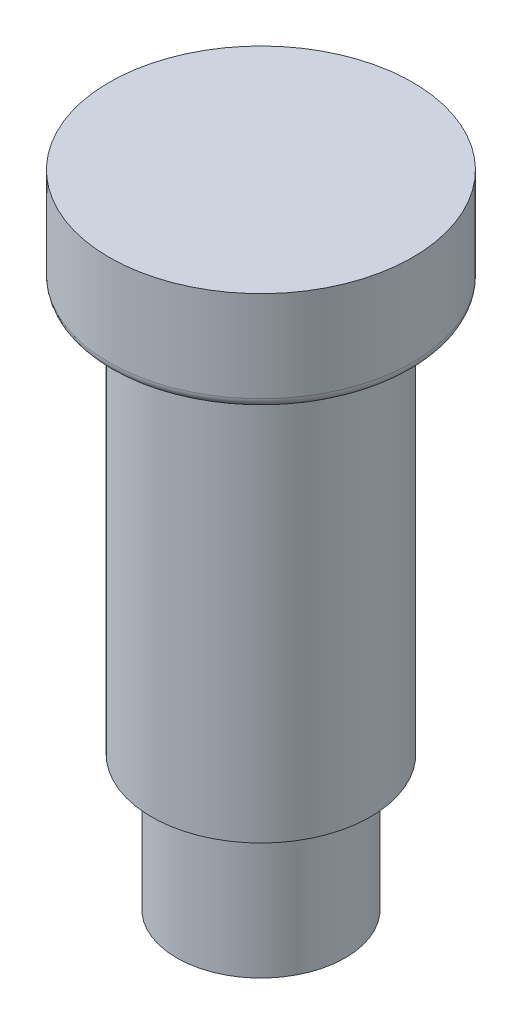
SolidWorks part; units mm, degrees
material "AISI 1020"
ref_plane "Plano superior" through (0, 0, 0) normal (0, 0, 1) x (1, 0, 0)
ref_plane "Plano frontal" through (0, 0, 0) normal (0, 1, 0) x (1, 0, 0)
ref_plane "Plano direito" through (0, 0, 0) normal (1, 0, 0) x (0, 0, -1)
sketch "Esboço1" plane through (0, 0, 0) normal (0, 1, 0) x (1, 0, 0)
  circle A0 centre (0, 0) radius 4.5
  dimension "D1" = 9
extrude "Ressalto-extrusão1" add sketch "Esboço1" along normal blind 3
sketch "Esboço2" plane through (0, 0, 0) normal (0, -1, 0) x (1, 0, 0)
  circle A0 centre (0, 0) radius 3.25
  dimension "D1" = 6.5
extrude "Ressalto-extrusão2" add sketch "Esboço2" along normal blind 12
sketch "Esboço3" plane through (0, -12, 0) normal (0, -1, 0) x (1, 0, 0)
  circle A0 centre (0, 0) radius 2.5
  dimension "D1" = 5
extrude "Ressalto-extrusão3" add sketch "Esboço3" along normal blind 4
fillet "Filete2" radius 0.3 1 edges at (0, 0, 4.5)
